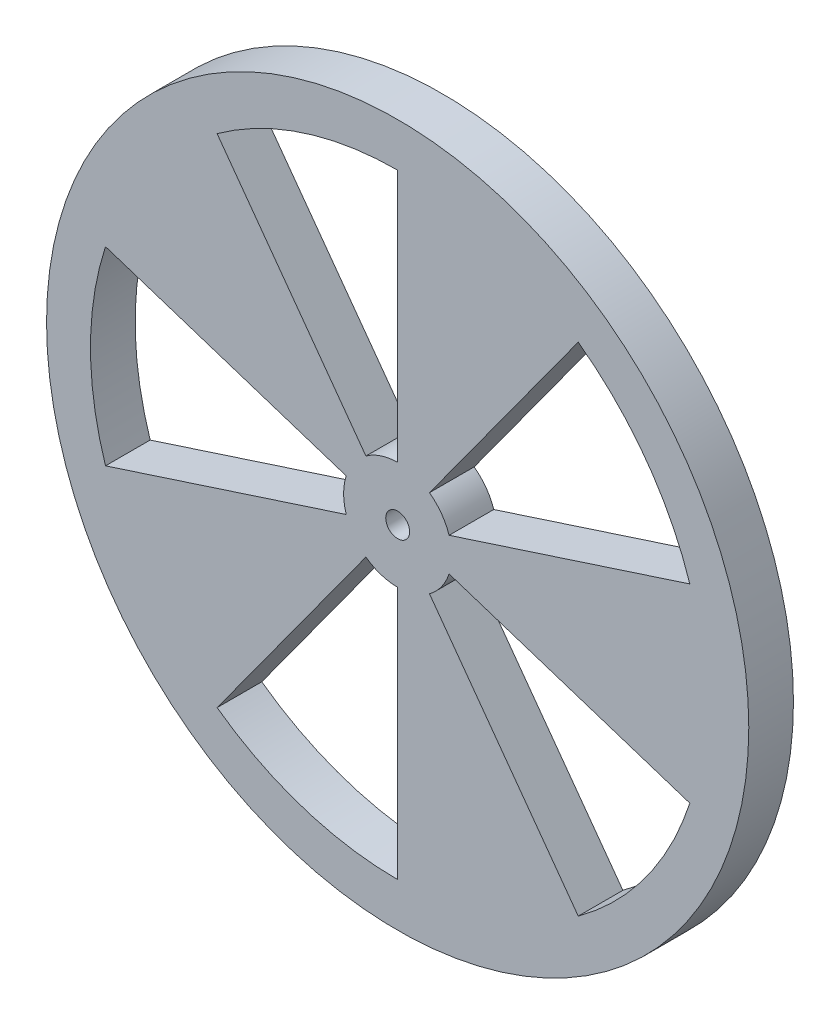
SolidWorks part; units mm, degrees
ref_plane "Front Plane" through (0, 0, 0) normal (0, 0, 1) x (1, 0, 0)
ref_plane "Top Plane" through (0, 0, 0) normal (0, 1, 0) x (1, 0, 0)
ref_plane "Right Plane" through (0, 0, 0) normal (1, 0, 0) x (0, 0, -1)
sketch "Sketch1" plane through (0, 0, 0) normal (0, 0, 1) x (1, 0, 0)
  circle A0 centre (0, 0) radius 25
  circle A1 centre (0, 0) radius 0.85
  dimension "D1" = 50
extrude "Boss-Extrude1" add sketch "Sketch1" along normal blind 3.18
sketch "Sketch2" plane through (0, 0, 3.18) normal (0, 0, 1) x (1, 0, 0)
  line L0 (0, 3.85) -> (0, 22)
  line L1 (2.263, 3.1147) -> (12.9313, 17.7984)
  line L2 (3.6616, 1.1897) -> (20.9232, 6.7984)
  line L3 (3.6616, -1.1897) -> (20.9232, -6.7984)
  line L4 (2.263, -3.1147) -> (12.9313, -17.7984)
  line L5 (0, -3.85) -> (0, -22)
  line L6 (-2.263, -3.1147) -> (-12.9313, -17.7984)
  line L7 (-3.6616, -1.1897) -> (-20.9232, -6.7984)
  line L8 (-3.6616, 1.1897) -> (-20.9232, 6.7984)
  line L9 (-2.263, 3.1147) -> (-12.9313, 17.7984)
  circle A0 centre (0, 0) radius 3.85
  circle A1 centre (0, 0) radius 22
  circle A2 centre (0, 0) radius 25 construction
  circle A3 centre (0, 0) radius 0.85 construction
  circle A4 centre (0, 0) radius 22
  circle A6 centre (0, 0) radius 21.8718
  arc A15 (-10.2309, -13.5768) -> (-9.9923, -13.7533) centre (0, 0) ccw
  arc A16 (-10.2309, -13.5768) -> (-9.9923, -13.7533) centre (0, 0) ccw
  arc A17 (-10.2309, -13.5768) -> (-9.9923, -13.7533) centre (0, 0) ccw
  arc A18 (-10.2309, -13.5768) -> (-9.9923, -13.7533) centre (0, 0) ccw
  arc A19 (-10.2309, -13.5768) -> (-9.9923, -13.7533) centre (0, 0) ccw
  arc A20 (-10.2309, -13.5768) -> (-9.9923, -13.7533) centre (0, 0) ccw
  arc A21 (-10.2309, -13.5768) -> (-9.9923, -13.7533) centre (0, 0) ccw
  arc A22 (-10.2309, -13.5768) -> (-9.9923, -13.7533) centre (0, 0) ccw
  arc A23 (-10.2309, -13.5768) -> (-9.9923, -13.7533) centre (0, 0) ccw
  arc A24 (-10.2309, -13.5768) -> (-9.9923, -13.7533) centre (0, 0) ccw
  arc A25 (-10.2309, -13.5768) -> (-9.9923, -13.7533) centre (0, 0) ccw
  arc A26 (-10.2309, -13.5768) -> (-9.9923, -13.7533) centre (0, 0) ccw
  arc A27 (-10.2309, -13.5768) -> (-9.9923, -13.7533) centre (0, 0) ccw
  arc A28 (-10.2309, -13.5768) -> (-9.9923, -13.7533) centre (0, 0) ccw
  arc A29 (-10.2309, -13.5768) -> (-9.9923, -13.7533) centre (0, 0) ccw
  arc A30 (-10.2309, -13.5768) -> (-9.9923, -13.7533) centre (0, 0) ccw
  arc A32 (-10.2309, -13.5768) -> (-9.9923, -13.7533) centre (0, 0) ccw
  point P34 (0, 0)
  point P42 (0, 0)
  point P101 (0, 0)
  dimension "D1" = 3
  dimension "D2" = 3
  dimension "D3" = 10
extrude "Cut-Extrude1" cut sketch "Sketch2" against normal through all contours L0 A1 L9 A0 | L8 A1 L7 A0 | L6 A1 L5 A0 | L4 A1 L3 A0 | L2 A1 L1 A0 | A27
